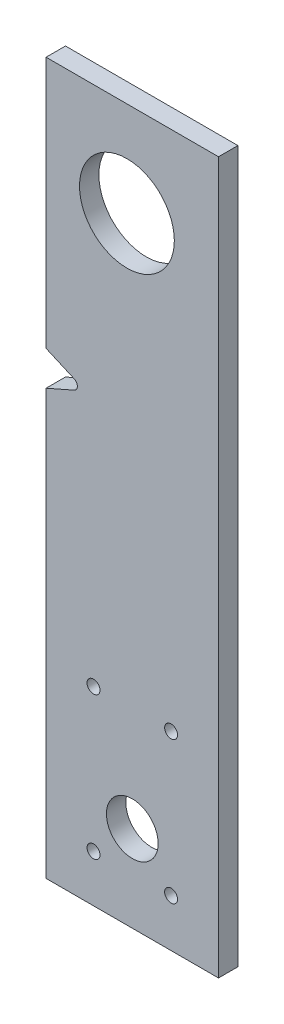
SolidWorks part; units mm, degrees
ref_plane "Front Plane" through (0, 0, 0) normal (0, 0, 1) x (1, 0, 0)
ref_plane "Top Plane" through (0, 0, 0) normal (0, 1, 0) x (1, 0, 0)
ref_plane "Right Plane" through (0, 0, 0) normal (1, 0, 0) x (0, 0, -1)
sketch "Sketch1" plane through (0, 0, 0) normal (0, 0, 1) x (1, 0, 0)
  line L1 (-21.25, 20) -> (21.25, 20)
  line L2 (-21.25, 20) -> (-21.25, -20)
  line L3 (-21.25, -20) -> (21.25, -20)
  line L4 (21.25, 20) -> (21.25, -20)
  line L5 (-21.25, 20) -> (21.25, -20) construction
  line L6 (-21.25, -20) -> (21.25, 20) construction
  point P0 (0, 0)
  dimension "D1" = 42.5
  dimension "D2" = 40
extrude "Boss-Extrude1" add sketch "Sketch1" along normal mid plane 4.5
sketch "Sketch3" plane through (0, 0, 2.25) normal (0, 0, 1) x (1, 0, 0)
  line L0 (21.25, -20) -> (21.25, 20) construction
  line L1 (-21.25, -20) -> (21.25, -20) construction
  circle A7 centre (1.25, 0) radius 6
  dimension "D2" = 20
  dimension "D1" = 20
  dimension "D3" = 12
extrude "Cut-Extrude2" cut sketch "Sketch3" against normal mid plane 10
sketch "Sketch4" plane through (0, 20, 0) normal (0, 1, 0) x (1, 0, 0)
  line L1 (-21.25, 2.25) -> (21.25, 2.25)
  line L2 (-21.25, 2.25) -> (-21.25, -2.25)
  line L3 (-21.25, -2.25) -> (21.25, -2.25)
  line L4 (21.25, 2.25) -> (21.25, -2.25)
extrude "Boss-Extrude2" add sketch "Sketch4" along normal blind 15
sketch "Sketch7" plane through (0, 0, 2.25) normal (0, 0, 1) x (1, 0, 0)
  circle A0 centre (-7.75, 24.0536) radius 1.5
  circle A1 centre (10.25, 24.0536) radius 1.5
  circle A2 centre (10.25, -8.9458) radius 1.5
  circle A3 centre (-7.75, -9.0539) radius 1.5
  circle A5 centre (1.25, 0) radius 6 construction
  point P2 (0, 0)
  point P5 (0, 0)
  point P8 (0, 0)
  point P12 (0, 0)
  point P13 (0, 0)
  point P14 (0, 0)
  point P15 (0, 0)
  point P16 (0, 0)
  point P18 (0, 0)
  dimension "D1" = 3
  dimension "D2" = 18
  dimension "D3" = 9
extrude "Cut-Extrude3" cut sketch "Sketch7" against normal blind 10
sketch "Sketch8" plane through (0, 0, 2.25) normal (0, 0, 1) x (1, 0, 0)
  line L0 (-21.25, -20) -> (21.25, -20) construction
  line L1 (-18.75, -20) -> (-21.25, -20)
  line L2 (-18.75, -20) -> (-18.75, 35)
  line L3 (-18.75, 35) -> (-21.25, 35)
  line L4 (-21.25, -20) -> (-21.25, 35)
  dimension "D1" = 2.5
extrude "Cut-Extrude4" cut sketch "Sketch8" against normal blind 10
sketch "Sketch9" plane through (0, 35, 0) normal (0, 1, 0) x (1, 0, 0)
  line L1 (-18.75, 2.25) -> (21.25, 2.25)
  line L2 (-18.75, 2.25) -> (-18.75, -2.25)
  line L3 (-18.75, -2.25) -> (21.25, -2.25)
  line L4 (21.25, 2.25) -> (21.25, -2.25)
extrude "Boss-Extrude3" add sketch "Sketch9" along normal blind 110
sketch "Sketch11" plane through (0, 0, -2.25) normal (0, 0, -1) x (-1, 0, 0)
  line L0 (-21.25, 145) -> (18.75, 145) construction
  circle A0 centre (0, 123) radius 11
  point P4 (0, 113)
  point P5 (3.7288, 113)
  dimension "D1" = 22
  dimension "D2" = 22
extrude "Cut-Extrude5" cut sketch "Sketch11" against normal blind 100
sketch "Sketch12" plane through (0, 0, -2.25) normal (0, 0, -1) x (-1, 0, 0)
  line L0 (-21.25, 145) -> (18.75, 145) construction
  line L1 (9.6411, 82.5) -> (18.75, 78.5)
  line L2 (18.75, -20) -> (18.75, 145) construction
  line L3 (18.75, 86.5) -> (9.6411, 82.5)
  line L4 (12.75, 82.5) -> (18.75, 82.5) construction
  circle A0 centre (12.75, 82.5) radius 1.25
  point P4 (0, 0)
  point P9 (7.0041, 82.5)
  point P10 (9.0538, 83.2498)
  point P12 (7.29, 82.6585)
  point P13 (6.67, 82.5)
  dimension "D2" = 2.5
  dimension "D1" = 62.5
  dimension "D3" = 6
  dimension "D4" = 4
extrude "Cut-Extrude6" cut sketch "Sketch12" against normal blind 100
